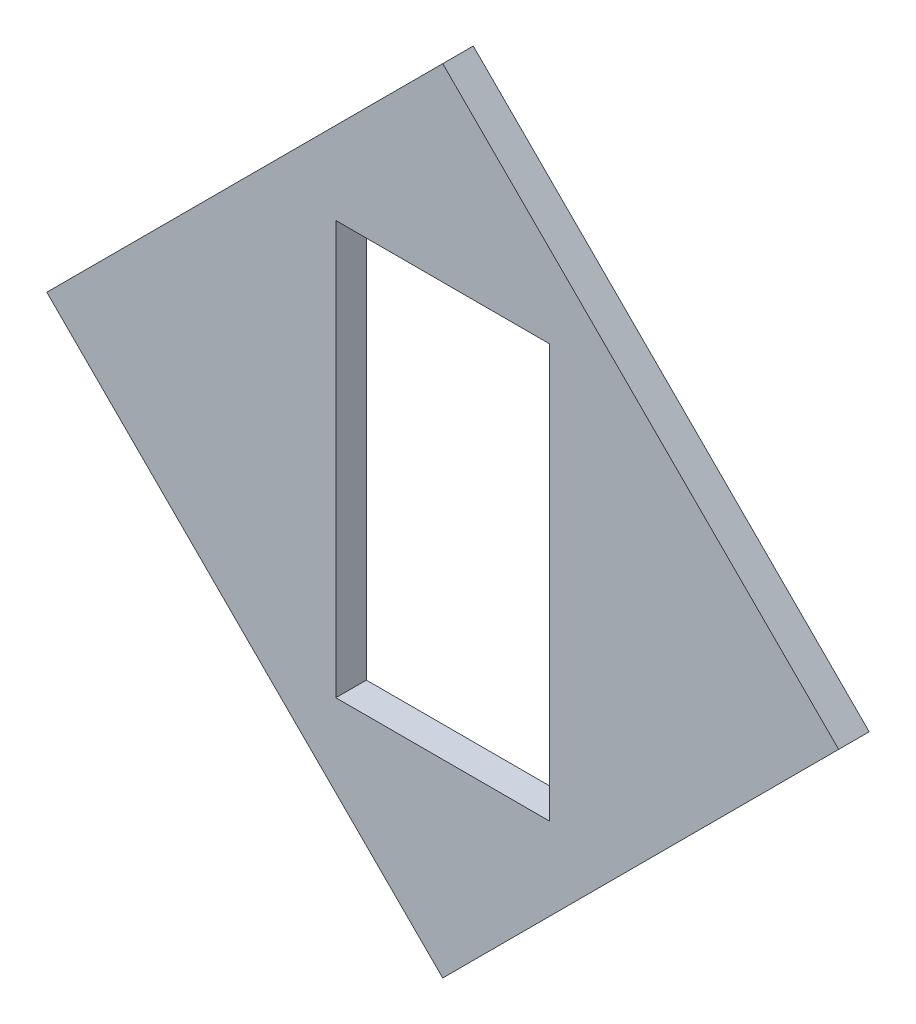
SolidWorks part; units mm, degrees
ref_plane "Front Plane" through (0, 0, 0) normal (0, 0, 1) x (1, 0, 0)
ref_plane "Top Plane" through (0, 0, 0) normal (0, 1, 0) x (1, 0, 0)
ref_plane "Right Plane" through (0, 0, 0) normal (1, 0, 0) x (0, 0, -1)
sketch "Sketch1" plane through (0, 0, 0) normal (0, 0, 1) x (1, 0, 0)
  line L1 (-38.8909, 0) -> (0, 38.8909)
  line L2 (-38.8909, 0) -> (0, -38.8909)
  line L3 (0, -38.8909) -> (38.8909, 0)
  line L4 (0, 38.8909) -> (38.8909, 0)
  line L5 (-38.8909, 0) -> (38.8909, 0) construction
  line L6 (0, -38.8909) -> (0, 38.8909) construction
  point P0 (0, 0)
  dimension "D1" = 55
  dimension "D2" = 55
extrude "Boss-Extrude1" add sketch "Sketch1" along normal blind 3
sketch "Sketch2" plane through (0, 0, 3) normal (0, 0, 1) x (1, 0, 0)
  line L1 (10.5, -20.3) -> (-10.5, -20.3)
  line L2 (10.5, -20.3) -> (10.5, 20.3)
  line L3 (10.5, 20.3) -> (-10.5, 20.3)
  line L4 (-10.5, -20.3) -> (-10.5, 20.3)
  line L5 (10.5, -20.3) -> (-10.5, 20.3) construction
  line L6 (10.5, 20.3) -> (-10.5, -20.3) construction
  point P0 (0, 0)
  dimension "D1" = 21
  dimension "D2" = 40.6
extrude "Cut-Extrude1" cut sketch "Sketch2" against normal blind 3
